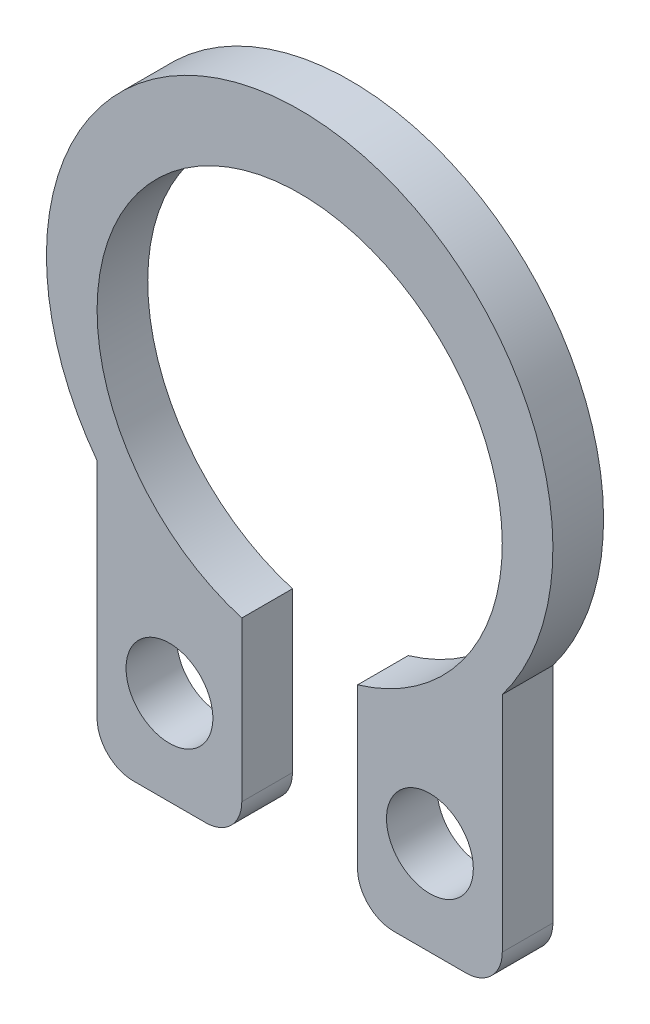
SolidWorks part; units mm, degrees
material "1023 Arkusz stali węglowej (SS)"
ref_plane "Płaszczyzna przednia" through (0, 0, 0) normal (0, 0, 1) x (1, 0, 0)
ref_plane "Płaszczyzna górna" through (0, 0, 0) normal (0, 1, 0) x (1, 0, 0)
ref_plane "Płaszczyzna prawa" through (0, 0, 0) normal (1, 0, 0) x (0, 0, -1)
sketch "Szkic1" plane through (0, 0, 0) normal (0, 0, 1) x (1, 0, 0)
  line L0 (0, 0) -> (0, -4.8525) construction
  line L1 (0.8, -2.6833) -> (0.8, -4.8833)
  line L2 (1.3, -5.3833) -> (2.3, -5.3833)
  line L3 (2.8, -4.8833) -> (2.8, -1.8)
  line L4 (-0.8, -2.6833) -> (-0.8, -4.8833)
  line L5 (-2.8, -4.8833) -> (-2.8, -1.8)
  line L6 (-1.3, -5.3833) -> (-2.3, -5.3833)
  arc A0 (0.8, -2.6833) -> (-0.8, -2.6833) centre (0, 0) ccw
  arc A1 (2.8, -1.8) -> (-2.8, -1.8) centre (0, 0.3) ccw
  circle A2 centre (1.8, -4.0833) radius 0.6
  arc A3 (2.3, -5.3833) -> (2.8, -4.8833) centre (2.3, -4.8833) ccw
  arc A4 (0.8, -4.8833) -> (1.3, -5.3833) centre (1.3, -4.8833) ccw
  arc A5 (-0.8, -4.8833) -> (-1.3, -5.3833) centre (-1.3, -4.8833) cw
  arc A6 (-2.3, -5.3833) -> (-2.8, -4.8833) centre (-2.3, -4.8833) cw
  circle A7 centre (-1.8, -4.0833) radius 0.6
  point P13 (2.8, -5.3833)
  point P16 (0.8, -5.3833)
  point P27 (-0.8, -5.3833)
  point P28 (-2.8, -5.3833)
  dimension "D1" = 1
  dimension "D2" = 1.3
  dimension "D3" = 2.7
  dimension "D4" = 1.2
  dimension "D6" = 0.5
  dimension "D5" = 2
  dimension "D7" = 0.8
extrude "Dodanie-wyciągnięcie1" add sketch "Szkic1" along normal blind 0.7
